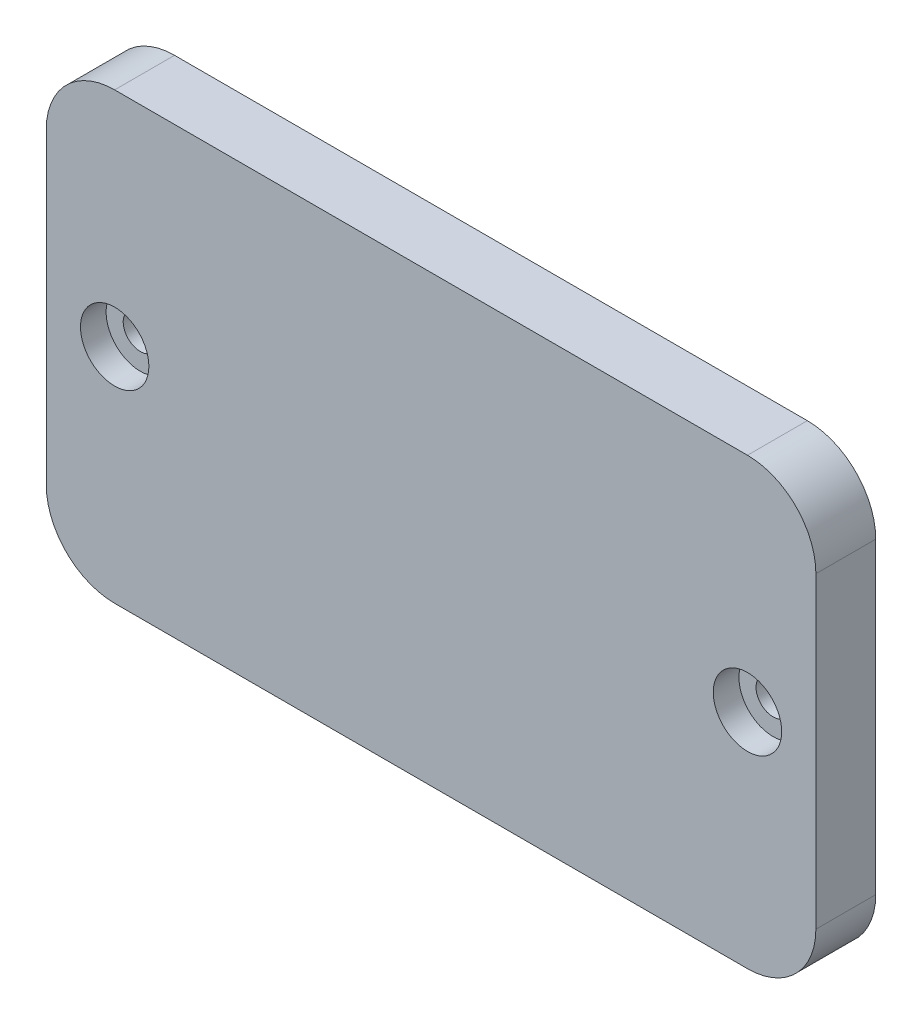
SolidWorks part; units mm, degrees
ref_plane "Front Plane" through (0, 0, 0) normal (0, 0, 1) x (1, 0, 0)
ref_plane "Top Plane" through (0, 0, 0) normal (0, 1, 0) x (1, 0, 0)
ref_plane "Right Plane" through (0, 0, 0) normal (1, 0, 0) x (0, 0, -1)
sketch "Sketch1" plane through (0, 0, 0) normal (0, 0, 1) x (1, 0, 0)
  line L1 (-4, 13) -> (41, 13)
  line L2 (-4, 13) -> (-4, -13)
  line L3 (-4, -13) -> (41, -13)
  line L4 (41, 13) -> (41, -13)
  circle A0 centre (0, 0) radius 1
  circle A1 centre (37, 0) radius 1
  dimension "D1" = 2
  dimension "D2" = 2
  dimension "D3" = 37
  dimension "D4" = 13
  dimension "D5" = 13
  dimension "D6" = 4
  dimension "D7" = 4
extrude "Boss-Extrude1" add sketch "Sketch1" along normal blind 3.5
fillet "Fillet1" radius 4 4 edges at (41, -13, 1.75) (-4, -13, 1.75) (-4, 13, 1.75) (41, 13, 1.75)
sketch "Sketch2" plane through (0, 0, 3.5) normal (0, 0, 1) x (1, 0, 0)
  circle A0 centre (0, 0) radius 2
  circle A1 centre (37, 0) radius 2
  dimension "D1" = 4
extrude "Cut-Extrude1" cut sketch "Sketch2" against normal blind 1.5
